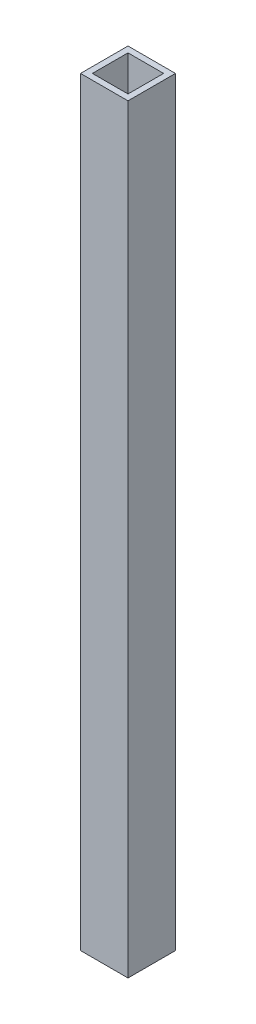
SolidWorks part; units mm, degrees
ref_plane "Front Plane" through (0, 0, 0) normal (0, 0, 1) x (1, 0, 0)
ref_plane "Top Plane" through (0, 0, 0) normal (0, 1, 0) x (1, 0, 0)
ref_plane "Right Plane" through (0, 0, 0) normal (1, 0, 0) x (0, 0, -1)
sketch "Sketch1" plane through (0, 0, 0) normal (0, 0, 1) x (1, 0, 0)
  line L0 (0.6089, -212.9418) -> (0.6089, 214.6824) construction
  line L2 (-12.0911, 193.4582) -> (-12.0911, -212.9418)
  line L3 (-12.0911, -212.9418) -> (13.3089, -212.9418)
  line L4 (13.3089, 193.4582) -> (13.3089, -212.9418)
  line L5 (-12.0911, 193.4582) -> (13.3089, -212.9418) construction
  line L6 (-12.0911, -212.9418) -> (12.3026, 216.6658) construction
  line L10 (-12.0911, 193.4582) -> (13.3089, 193.4582)
  point P0 (0, 0)
  dimension "D1" = 406.4
  dimension "D2" = 25.4
  dimension "D3" = 25.4
extrude "Boss-Extrude1" add sketch "Sketch1" along normal mid plane 25.4
sketch "Sketch2" plane through (0, -212.9418, 0) normal (0, -1, 0) x (1, 0, 0)
  line L8 (-8.9161, -9.525) -> (10.1339, -9.525)
  line L9 (10.1339, -9.525) -> (10.1339, 9.525)
  line L10 (10.1339, 9.525) -> (-8.9161, 9.525)
  line L11 (-8.9161, 9.525) -> (-8.9161, -9.525)
  line L12 (-8.9161, -9.525) -> (10.1339, -9.525)
  line L13 (10.1339, -9.525) -> (10.1339, 9.525)
  line L14 (10.1339, 9.525) -> (-8.9161, 9.525)
  line L15 (-8.9161, 9.525) -> (-8.9161, -9.525)
  dimension "D1" = 3.175
extrude "Cut-Extrude1" cut sketch "Sketch2" against normal through all
